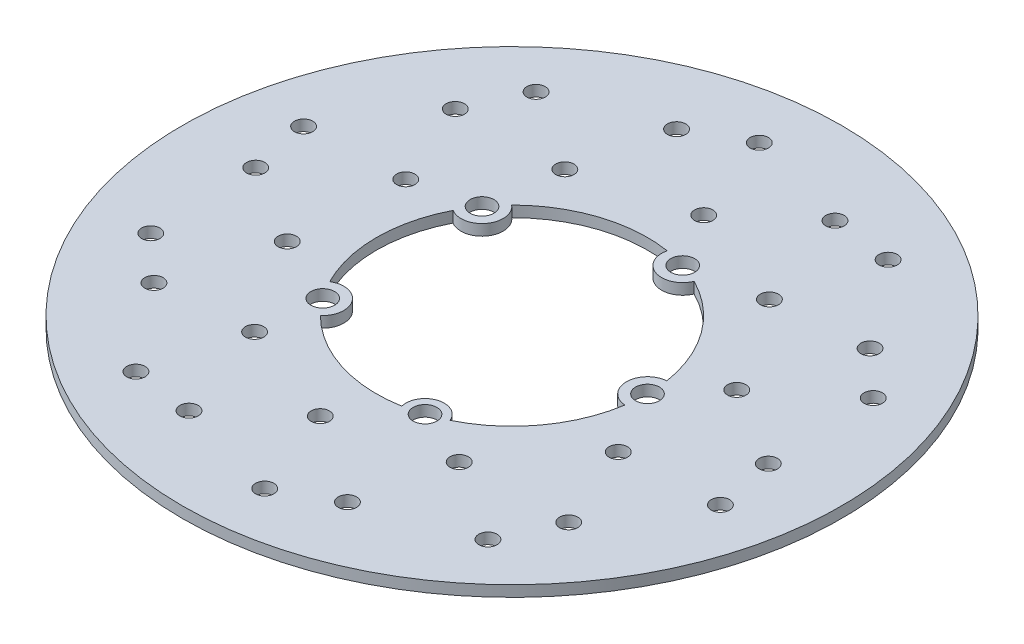
SolidWorks part; units mm, degrees
material "Alloy Steel (SS)"
ref_plane "Front Plane" through (0, 0, 0) normal (0, 0, 1) x (1, 0, 0)
ref_plane "Top Plane" through (0, 0, 0) normal (0, 1, 0) x (1, 0, 0)
ref_plane "Right Plane" through (0, 0, 0) normal (1, 0, 0) x (0, 0, -1)
sketch "Sketch1" plane through (0, 0, 0) normal (0, 1, 0) x (1, 0, 0)
  line L0 (-325.1112, -164.1814) -> (-16.8347, -164.1814) construction
  circle A0 centre (0, 0) radius 90
  arc A2 (-32.9417, 16.8477) -> (-32.9417, -16.8477) centre (0, 0) ccw
  circle A3 centre (37, 0) radius 3.25
  circle A4 centre (11.4336, -35.1891) radius 3.25
  circle A5 centre (-29.9336, -21.7481) radius 3.25
  circle A6 centre (-29.9336, 21.7481) radius 3.25
  circle A7 centre (11.4336, 35.1891) radius 3.25
  arc A8 (36.5532, 5.7326) -> (36.5532, -5.7326) centre (37, 0) ccw
  arc A9 (5.8435, 36.5356) -> (16.7476, 32.9927) centre (11.4336, 35.1891) ccw
  arc A10 (-32.9417, 16.8477) -> (-26.2026, 26.1232) centre (-29.9336, 21.7481) ccw
  arc A11 (-26.2026, -26.1232) -> (-32.9417, -16.8477) centre (-29.9336, -21.7481) ccw
  arc A12 (16.299, -33.2166) -> (6.3381, -36.4531) centre (11.4336, -35.1891) ccw
  arc A13 (-26.2026, -26.1232) -> (6.3381, -36.4531) centre (0, 0) ccw
  circle A14 centre (-29.9336, 21.7481) radius 5.75 construction
  circle A15 centre (-29.9336, -21.7481) radius 5.75 construction
  arc A16 (16.299, -33.2166) -> (36.5532, -5.7326) centre (0, 0) ccw
  circle A17 centre (11.4336, -35.1891) radius 5.25 construction
  arc A18 (36.5532, 5.7326) -> (16.7476, 32.9927) centre (0, 0) ccw
  arc A19 (5.8435, 36.5356) -> (-26.2026, 26.1232) centre (0, 0) ccw
  circle A21 centre (11.4336, 35.1891) radius 5.75 construction
  circle A22 centre (37, 0) radius 5.75 construction
  point P4 (-24.4349, -20.0669)
  point P18 (0, 0)
  point P20 (42.4988, 1.6811)
  point P24 (16.6836, -35.1891)
  point P27 (-24.4349, 23.4292)
  point P39 (16.9324, 36.8702)
  dimension "D1" = 180
  dimension "D2" = 74
  dimension "D3" = 6.5
  dimension "D5" = 41.3673
  dimension "D6" = 13.441
  dimension "D7" = 2.5
  dimension "D8" = 2
  dimension "D4" = 5
extrude "Boss-Extrude1" add sketch "Sketch1" along normal blind 3 contours A0 A19 A9 A18 A8 A16 A12 A13 A11 A2 A10 A7 A6 A5 A4
sketch "Sketch2" plane through (0, 3, 0) normal (0, 1, 0) x (1, 0, 0)
  line L0 (0, 0) -> (70, 0) construction
  line L1 (0, 0) -> (48.2442, 13.1338) construction
  line L2 (0, 0) -> (68.8063, 29.8445) construction
  circle A0 centre (70, 0) radius 2.5
  circle A1 centre (48.2442, 13.1338) radius 2.5
  circle A2 centre (68.8063, 29.8445) radius 2.5
  circle A3 centre (73.2076, -16.2987) radius 2.5
  circle A4 centre (46.7502, -17.7318) radius 2.5
  circle A5 centre (56.6312, -41.145) radius 2.5
  circle A6 centre (49.6461, -56.2162) radius 2.5
  circle A7 centre (27.3992, -41.8244) radius 2.5
  circle A8 centre (21.6312, -66.574) radius 2.5
  circle A9 centre (7.1215, -74.6611) radius 2.5
  circle A10 centre (-2.4173, -49.9415) radius 2.5
  circle A11 centre (-21.6312, -66.574) radius 2.5
  circle A12 centre (-38.1233, -64.588) radius 2.5
  circle A13 centre (-31.3105, -38.9827) radius 2.5
  circle A14 centre (-56.6312, -41.145) radius 2.5
  circle A15 centre (-68.8063, -29.8445) radius 2.5
  circle A16 centre (-48.2442, -13.1338) radius 2.5
  circle A17 centre (-70, 0) radius 2.5
  circle A18 centre (-73.2076, 16.2987) radius 2.5
  circle A19 centre (-46.7502, 17.7318) radius 2.5
  circle A20 centre (-56.6312, 41.145) radius 2.5
  circle A21 centre (-49.6461, 56.2162) radius 2.5
  circle A22 centre (-27.3992, 41.8244) radius 2.5
  circle A23 centre (-21.6312, 66.574) radius 2.5
  circle A24 centre (-7.1215, 74.6611) radius 2.5
  circle A25 centre (2.4173, 49.9415) radius 2.5
  circle A26 centre (21.6312, 66.574) radius 2.5
  circle A27 centre (38.1233, 64.588) radius 2.5
  circle A28 centre (31.3105, 38.9827) radius 2.5
  circle A29 centre (56.6312, 41.145) radius 2.5
  point P65 (0, 0)
  dimension "D1" = 5
  dimension "D2" = 70
  dimension "D3" = 75
  dimension "D4" = 50
  dimension "D5" = 25.4128
  dimension "D6" = 26.4962
extrude "Cut-Extrude1" cut sketch "Sketch2" against normal blind 3
